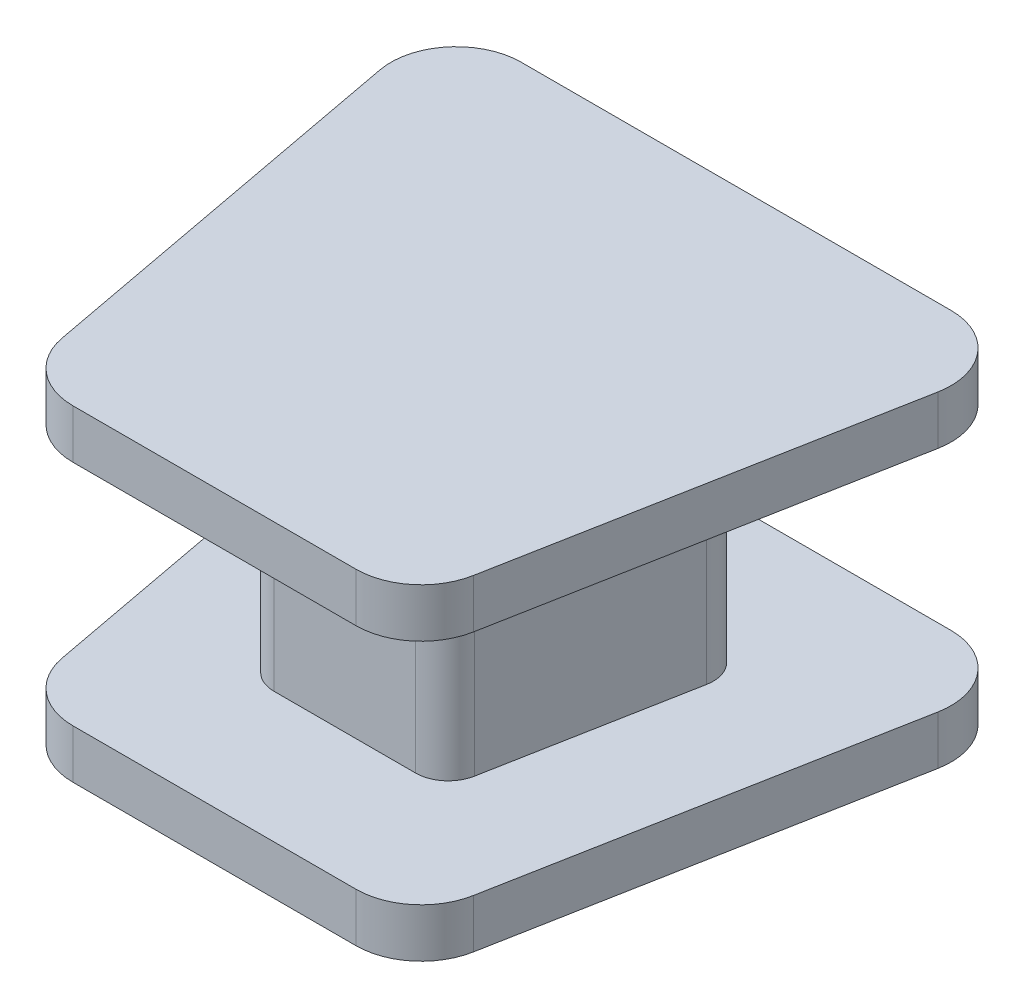
SolidWorks part; units mm, degrees
ref_plane "Front Plane" through (0, 0, 0) normal (0, 0, 1) x (1, 0, 0)
ref_plane "Top Plane" through (0, 0, 0) normal (0, 1, 0) x (1, 0, 0)
ref_plane "Right Plane" through (0, 0, 0) normal (1, 0, 0) x (0, 0, -1)
sketch "Sketch1" plane through (0, 0, 0) normal (0, 1, 0) x (1, 0, 0)
  line L0 (-16.739, 20.32) -> (16.739, 20.32)
  line L1 (-11.024, -20.32) -> (11.024, -20.32)
  line L2 (0, 20.32) -> (0, -20.32) construction
  line L3 (16.017, -16.1762) -> (21.732, 14.3038)
  line L4 (-16.017, -16.1762) -> (-21.732, 14.3038)
  arc A0 (16.017, -16.1762) -> (11.024, -20.32) centre (11.024, -15.24) cw
  arc A1 (16.739, 20.32) -> (21.732, 14.3038) centre (16.739, 15.24) cw
  arc A2 (-16.017, -16.1762) -> (-11.024, -20.32) centre (-11.024, -15.24) ccw
  arc A3 (-16.739, 20.32) -> (-21.732, 14.3038) centre (-16.739, 15.24) ccw
  point P6 (15.24, -20.32)
  point P9 (22.86, 20.32)
  dimension "D3" = 5.08
  dimension "D4" = 5.08
  dimension "D1" = 22.86
  dimension "D2" = 15.24
  dimension "D5" = 20.32
  dimension "D6" = 20.32
extrude "Boss-Extrude1" add sketch "Sketch1" along normal mid plane 25.4
sketch "Sketch3" plane through (0, 0, 0) normal (0, 1, 0) x (1, 0, 0)
  line L0 (-16.739, 20.32) -> (16.739, 20.32)
  line L1 (-11.024, -20.32) -> (11.024, -20.32)
  line L2 (0, 20.32) -> (0, -20.32) construction
  line L3 (16.017, -16.1762) -> (21.732, 14.3038)
  line L4 (-16.017, -16.1762) -> (-21.732, 14.3038)
  line L5 (5.512, -10.16) -> (-5.512, -10.16)
  line L6 (8.3695, 10.16) -> (-8.3695, 10.16)
  line L7 (-10.866, 7.1519) -> (-8.0085, -8.0881)
  line L8 (10.866, 7.1519) -> (8.0085, -8.0881)
  arc A0 (16.017, -16.1762) -> (11.024, -20.32) centre (11.024, -15.24) cw
  arc A1 (16.739, 20.32) -> (21.732, 14.3038) centre (16.739, 15.24) cw
  arc A2 (-16.017, -16.1762) -> (-11.024, -20.32) centre (-11.024, -15.24) ccw
  arc A3 (-16.739, 20.32) -> (-21.732, 14.3038) centre (-16.739, 15.24) ccw
  arc A4 (-8.3695, 10.16) -> (-10.866, 7.1519) centre (-8.3695, 7.62) ccw
  arc A5 (-8.0085, -8.0881) -> (-5.512, -10.16) centre (-5.512, -7.62) ccw
  arc A6 (8.0085, -8.0881) -> (5.512, -10.16) centre (5.512, -7.62) cw
  arc A7 (8.3695, 10.16) -> (10.866, 7.1519) centre (8.3695, 7.62) cw
  point P6 (15.24, -20.32)
  point P9 (22.86, 20.32)
  point P24 (-11.43, 10.16)
  point P27 (-7.62, -10.16)
  point P29 (0, -10.16)
  point P34 (0, 10.16)
  dimension "D3" = 5.08
  dimension "D4" = 5.08
  dimension "D9" = 2.54
  dimension "D10" = 2.54
  dimension "D1" = 22.86
  dimension "D2" = 15.24
  dimension "D5" = 11.43
  dimension "D6" = 7.62
  dimension "D7" = 10.16
  dimension "D8" = 10.16
extrude "Cut-Extrude1" cut sketch "Sketch3" against normal mid plane 17.78
